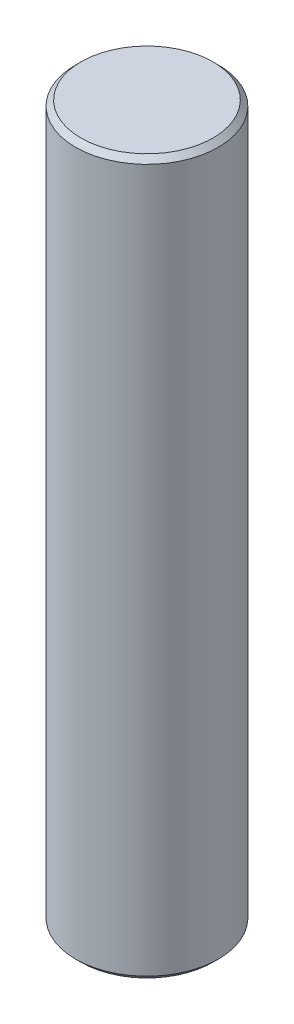
SolidWorks part; units mm, degrees
material "Stainless Steel (ferritic)"
ref_plane "Front Plane" through (0, 0, 0) normal (0, 0, 1) x (1, 0, 0)
ref_plane "Top Plane" through (0, 0, 0) normal (0, 1, 0) x (1, 0, 0)
ref_plane "Right Plane" through (0, 0, 0) normal (1, 0, 0) x (0, 0, -1)
sketch "Sketch1" plane through (0, 0, 0) normal (0, 1, 0) x (1, 0, 0)
  circle A0 centre (0, 0) radius 2
  dimension "D1" = 4
extrude "Boss-Extrude1" add sketch "Sketch1" along normal blind 20
chamfer "Chamfer1" distance 0.15 angle 45 2 edges at (0, 0, 2) (0, 20, 2)
